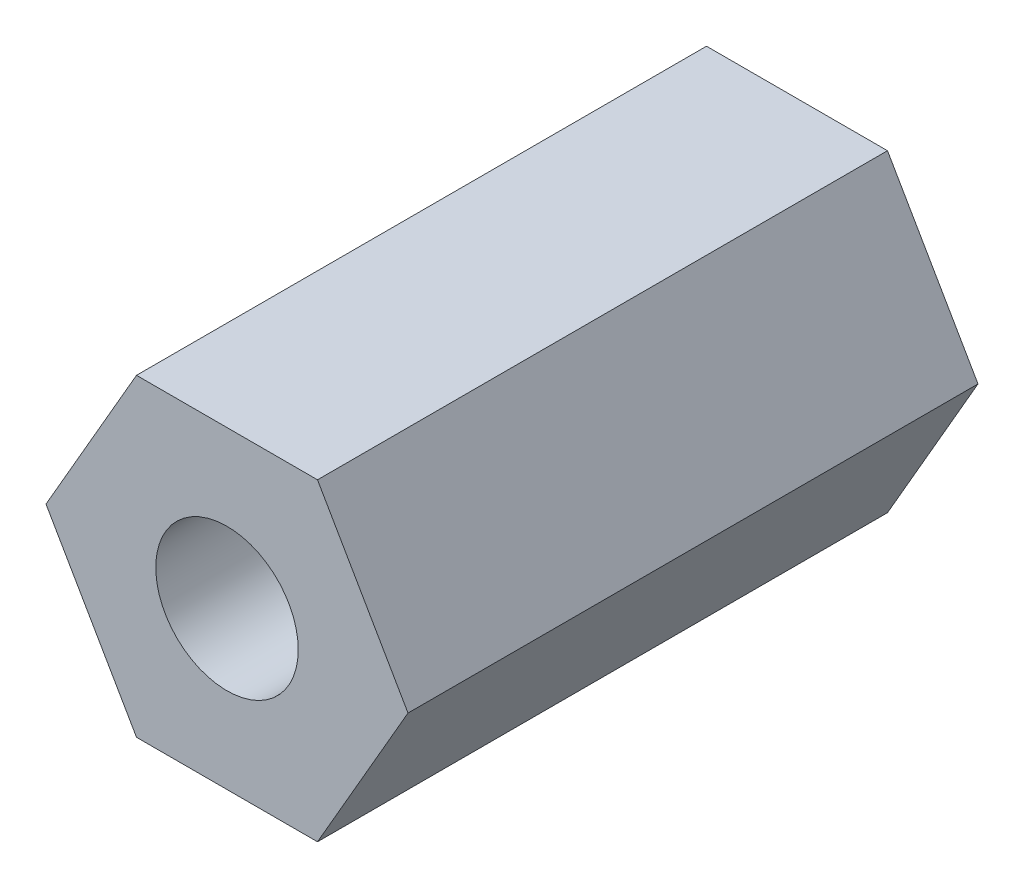
SolidWorks part; units mm, degrees
ref_plane "前视基准面" through (0, 0, 0) normal (0, 0, 1) x (1, 0, 0)
ref_plane "上视基准面" through (0, 0, 0) normal (0, 1, 0) x (1, 0, 0)
ref_plane "右视基准面" through (0, 0, 0) normal (1, 0, 0) x (0, 0, -1)
other "Configuration Table"
sketch "5.5 mm across flats and M3 tap bore" plane through (0, 0, 0) normal (0, 0, 1) x (1, 0, 0)
  line L0 (3.1754, 0) -> (1.5877, 2.75)
  line L1 (1.5877, 2.75) -> (-1.5877, 2.75)
  line L2 (-1.5877, 2.75) -> (-3.1754, 0)
  line L3 (-3.1754, 0) -> (-1.5877, -2.75)
  line L4 (-1.5877, -2.75) -> (1.5877, -2.75)
  line L5 (1.5877, -2.75) -> (3.1754, 0)
  circle A0 centre (0, 0) radius 1.25
extrude "M3 female-female brass spacer 10 mm" add sketch "5.5 mm across flats and M3 tap bore" along normal blind 10
